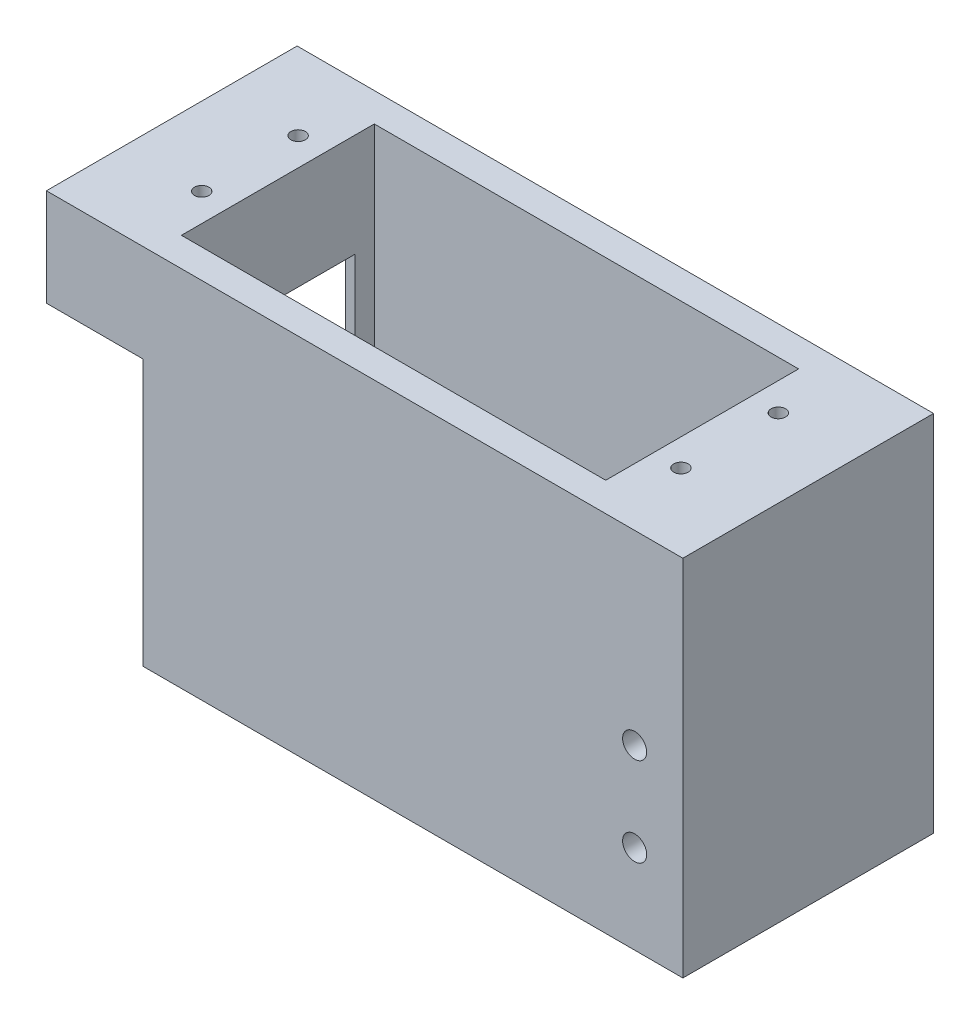
SolidWorks part; units mm, degrees
ref_plane "Front Plane" through (0, 0, 0) normal (0, 0, 1) x (1, 0, 0)
ref_plane "Top Plane" through (0, 0, 0) normal (0, 1, 0) x (1, 0, 0)
ref_plane "Right Plane" through (0, 0, 0) normal (1, 0, 0) x (0, 0, -1)
sketch "Sketch1" plane through (0, 0, 0) normal (0, 1, 0) x (1, 0, 0)
  line L1 (0, 0) -> (46, 0)
  line L2 (0, 0) -> (0, 26)
  line L3 (0, 26) -> (46, 26)
  line L4 (46, 0) -> (46, 26)
  dimension "D1" = 46
  dimension "D2" = 26
extrude "Boss-Extrude1" add sketch "Sketch1" along normal blind 27.6
sketch "Sketch2" plane through (0, 27.6, 0) normal (0, 1, 0) x (1, 0, 0)
  line L1 (-10, 26) -> (56, 26)
  line L2 (-10, 26) -> (-10, 0)
  line L3 (-10, 0) -> (56, 0)
  line L4 (56, 26) -> (56, 0)
  line L5 (0, 0) -> (46, 0) construction
  line L6 (0, 26) -> (0, 0) construction
  dimension "D1" = 66
  dimension "D2" = 26
  dimension "D3" = 0
  dimension "D4" = 10
extrude "Boss-Extrude2" add sketch "Sketch2" along normal blind 10.1
sketch "Sketch3" plane through (0, 37.7, 0) normal (0, 1, 0) x (1, 0, 0)
  line L0 (-10, 26) -> (-10, 0) construction
  line L1 (43, 3) -> (3, 3)
  line L2 (43, 3) -> (43, 23)
  line L3 (43, 23) -> (3, 23)
  line L4 (3, 3) -> (3, 23)
  line L6 (56, 26) -> (-10, 26) construction
  dimension "D1" = 40
  dimension "D2" = 20
  dimension "D3" = 13
  dimension "D4" = 3
extrude "Cut-Extrude2" cut sketch "Sketch3" against normal blind 25.5 contours L3 L4 L1 L2
hole_wizard "Ø1.5mm Dowel Hole2" positions "3DSketch3" profile "Sketch6" hole size "Ø1.5" standard "ANSI Metric"
sketch3d "3DSketch3"
  line L0 (56, 37.7, -26) -> (-10, 37.7, -26) construction
  line L1 (3, 37.7, -3) -> (3, 37.7, -23) construction
  line L2 (-10, 37.7, 0) -> (56, 37.7, 0) construction
  line L5 (43, 37.7, -3) -> (43, 37.7, -23) construction
  point P0 (-1.9, 37.7, -18)
  point P2 (-1.9, 37.7, -8)
  point P4 (47.8, 37.7, -8)
  point P6 (47.9, 37.7, -18)
  dimension "D1" = 8
  dimension "D2" = 4.9
  dimension "D3" = 8
  dimension "D4" = 8
  dimension "D5" = 8
  dimension "D6" = 4.8
  dimension "D8" = 10
  dimension "D7" = 4.9
sketch "Sketch6" plane through (-1.9, 37.7, -18) normal (1, 0, 0) x (0, 0, 1)
  line L0 (0, 0) -> (0, 9.4506)
  line L1 (0, 9.4506) -> (0.75, 9)
  line L2 (0.75, 9) -> (0.75, 0)
  line L5 (0.75, 0) -> (0, 0)
  line L10 (0, 9.4506) -> (-0.75, 9) construction
  line L11 (0, -6.35) -> (0, 107.95) construction
  dimension "Hole Dia." = 1.5
  dimension "Hole Depth" = 9
  dimension "Drill Angle" = 118
sketch "Sketch7" plane through (0, 0, 0) normal (-1, 0, 0) x (0, 0, 1)
  line L0 (-26, 27.6) -> (0, 27.6) construction
  line L1 (-21, 27) -> (-5, 27)
  line L2 (-21, 27) -> (-21, 12)
  line L3 (-21, 12) -> (-5, 12)
  line L4 (-5, 27) -> (-5, 12)
  line L5 (-26, 27.6) -> (-26, 0) construction
  line L6 (0, 27.6) -> (0, 0) construction
  line L7 (-26, 0) -> (0, 0) construction
  dimension "D1" = 0.6
  dimension "D2" = 5
  dimension "D3" = 5
  dimension "D4" = 12
sketch "Sketch8" plane through (0, 12.2, 0) normal (0, 1, 0) x (1, 0, 0)
  line L0 (43, 23) -> (3, 23) construction
  line L1 (3, 23) -> (43, 23)
  line L2 (3, 23) -> (3, 3)
  line L3 (3, 3) -> (43, 3)
  line L4 (43, 23) -> (43, 3)
  line L5 (3, 3) -> (3, 23) construction
  line L6 (43, 3) -> (3, 3) construction
extrude "Cut-Extrude6" cut sketch "Sketch8" against normal blind 3 contours L2 L1 L4 L3
extrude "Cut-Extrude8" cut sketch "Sketch7" against normal blind 3 contours L3 L4 L1 L2
sketch "Sketch9" plane through (0, 0, 0) normal (0, -1, 0) x (-1, 0, 0)
  line L1 (0, 26) -> (0, 0) construction
  line L2 (-46, 26) -> (0, 26) construction
  circle A0 centre (-13.05, 13) radius 10.9
  dimension "D1" = 21.8
  dimension "D3" = 13
  dimension "D2" = 13.05
extrude "Cut-Extrude9" cut sketch "Sketch9" against normal blind 7
sketch "Sketch10" plane through (0, 37.7, 0) normal (0, 1, 0) x (1, 0, 0)
  line L1 (1, 23) -> (45, 23)
  line L2 (1, 23) -> (1, 3)
  line L3 (1, 3) -> (45, 3)
  line L4 (45, 23) -> (45, 3)
  dimension "D1" = 44
  dimension "D2" = 20
extrude "Cut-Extrude10" cut sketch "Sketch10" against normal blind 28.5
sketch "Sketch11" plane through (46, 0, 0) normal (1, 0, 0) x (0, 0, -1)
  line L1 (0, 27.6) -> (26, 27.6)
  line L2 (0, 27.6) -> (0, 0)
  line L3 (0, 0) -> (26, 0)
  line L4 (26, 27.6) -> (26, 0)
extrude "Boss-Extrude3" add sketch "Sketch11" along normal blind 10 contours L2 L1 L4 L3
sketch "Sketch13" plane through (0, 0, 0) normal (0, 0, 1) x (1, 0, 0)
  line L3 (0, 0) -> (56, 0) construction
  line L4 (56, 37.7) -> (56, 0) construction
  circle A0 centre (51, 18.4) radius 1.25
  circle A1 centre (51, 9.2) radius 1.25
  point P10 (51, 18.4)
  point P12 (51, 9.2)
  dimension "D3" = 2.5
  dimension "D1" = 18.4
  dimension "D2" = 9.2
  dimension "D4" = 5
hole_wizard "Ø2.5mm Dowel Hole1" positions "3DSketch4" profile "Sketch14" hole size "Ø2.5" standard "ANSI Metric"
sketch3d "3DSketch4"
  point P0 (51, 18.4, 0)
  point P3 (51, 9.2, 0)
sketch "Sketch14" plane through (51, 18.4, 0) normal (1, 0, 0) x (0, -1, 0)
  line L0 (0, 0) -> (0, 26.7511)
  line L1 (0, 26.7511) -> (1.25, 26)
  line L2 (1.25, 26) -> (1.25, 0)
  line L5 (1.25, 0) -> (0, 0)
  line L10 (0, 26.7511) -> (-1.25, 26) construction
  line L11 (0, -6.35) -> (0, 107.95) construction
  dimension "Hole Dia." = 2.5
  dimension "Hole Depth" = 26
  dimension "Drill Angle" = 118
sketch "Sketch15" plane through (0, 0, 0) normal (0, -1, 0) x (1, 0, 0)
  line L0 (56, 0) -> (56, -26) construction
  line L1 (0, 0) -> (56, 0) construction
  circle A0 centre (51, -13) radius 1.4352
  point P0 (51, -13)
  dimension "D1" = 5
  dimension "D2" = 13
hole_wizard "Ø2.5mm Dowel Hole2" positions "Sketch15" profile "Sketch16" hole size "Ø2.5" standard "ANSI Metric"
sketch "Sketch16" plane through (51, 0, -13) normal (1, 0, 0) x (0, 0, -1)
  line L0 (0, 0) -> (0, 9.7511)
  line L1 (0, 9.7511) -> (1.25, 9)
  line L2 (1.25, 9) -> (1.25, 0)
  line L5 (1.25, 0) -> (0, 0)
  line L10 (0, 9.7511) -> (-1.25, 9) construction
  line L11 (0, -6.35) -> (0, 107.95) construction
  dimension "Hole Dia." = 2.5
  dimension "Hole Depth" = 9
  dimension "Drill Angle" = 118
